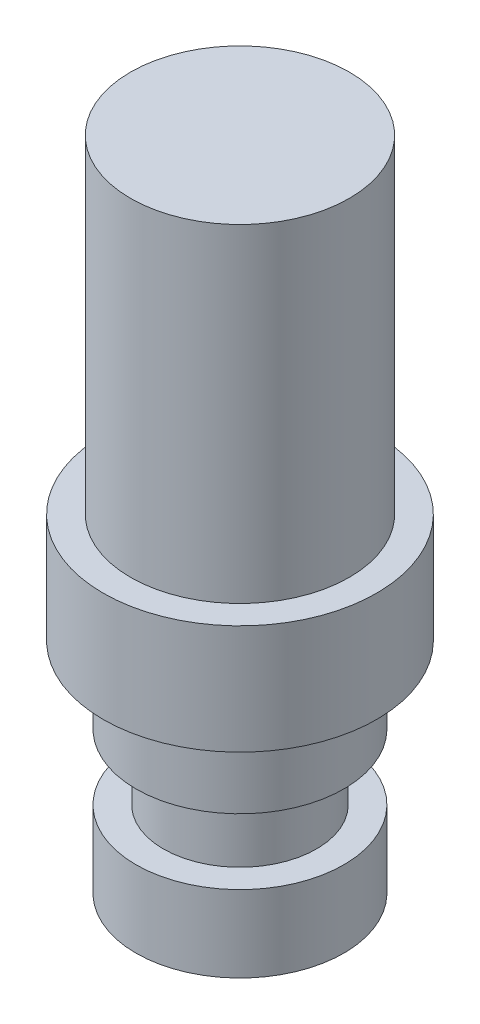
SolidWorks part; units mm, degrees
ref_plane "前视基准面" through (0, 0, 0) normal (0, 0, 1) x (1, 0, 0)
ref_plane "上视基准面" through (0, 0, 0) normal (0, 1, 0) x (1, 0, 0)
ref_plane "右视基准面" through (0, 0, 0) normal (1, 0, 0) x (0, 0, -1)
other "Configuration Table"
sketch "草图1" plane through (0, 0, 0) normal (0, 1, 0) x (1, 0, 0)
  circle A0 centre (0, 0) radius 9.5
  dimension "D1" = 19
extrude "凸台-拉伸1" add sketch "草图1" along normal blind 7
sketch "草图2" plane through (0, 0, 0) normal (0, 1, 0) x (1, 0, 0)
  circle A0 centre (0, 0) radius 7
  dimension "D1" = 14
extrude "凸台-拉伸2" add sketch "草图2" along normal blind 6 from surface at 7 starting at face at (0, 7, 9.5)
sketch "草图3" plane through (0, 0, 0) normal (0, 1, 0) x (1, 0, 0)
  circle A0 centre (0, 0) radius 9.5
  dimension "D1" = 19
extrude "凸台-拉伸3" add sketch "草图3" along normal blind 7 from surface at 13 starting at face at (0, 13, 7)
sketch "草图4" plane through (0, 0, 0) normal (0, 1, 0) x (1, 0, 0)
  circle A0 centre (0, 0) radius 12.5
  dimension "D1" = 25
extrude "凸台-拉伸4" add sketch "草图4" along normal blind 10 from surface at 20 starting at face at (0, 20, 9.5)
sketch "草图5" plane through (0, 0, 0) normal (0, 1, 0) x (1, 0, 0)
  circle A0 centre (0, 0) radius 10
  dimension "D1" = 20
extrude "凸台-拉伸5" add sketch "草图5" along normal blind 30 from surface at 30 starting at face at (0, 30, 12.5)
